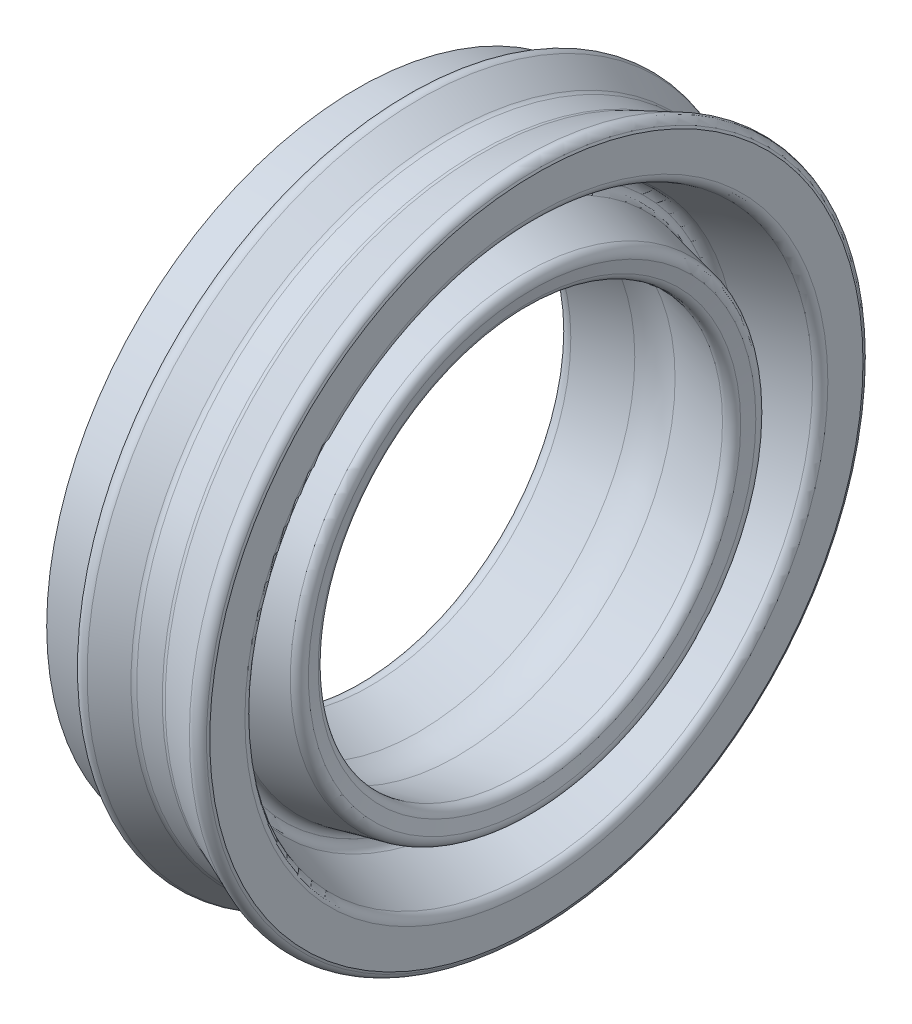
SolidWorks part; units mm, degrees
ref_plane "Alzado" through (0, 0, 0) normal (0, 0, 1) x (1, 0, 0)
ref_plane "Planta" through (0, 0, 0) normal (0, 1, 0) x (1, 0, 0)
ref_plane "Vista lateral" through (0, 0, 0) normal (1, 0, 0) x (0, 0, -1)
sketch "Croquis1" plane through (0, 0, 0) normal (0, 1, 0) x (1, 0, 0)
  line L0 (0, 0) -> (0, 6) construction
  line L1 (82.3658, 126.2926) -> (445.0325, 126.2926) construction
  line L2 (78.3557, 118.4737) -> (441.0224, 118.4737) construction
  line L3 (-2.1525, 8.367) -> (-1.0917, 8.367)
  line L4 (-1.0917, 8.367) -> (-0.805, 8.8728)
  line L5 (-0.4643, 8.9671) -> (0.2914, 8.5388)
  line L6 (0.4147, 8.5064) -> (1.1006, 8.5064)
  line L7 (1.1969, 8.5257) -> (2.3184, 8.994)
  line L8 (2.6455, 8.8596) -> (2.6711, 8.7983)
  line L9 (2.6711, 8.7983) -> (2.6711, 7.8514)
  line L10 (2.4959, 7.6128) -> (0.9249, 7.12)
  line L11 (0.7497, 6.8814) -> (0.7497, 6.8801)
  line L12 (0.9459, 6.636) -> (2.366, 6.3231)
  line L13 (2.5563, 6.0252) -> (2.4829, 5.6919)
  line L14 (2.1831, 5.502) -> (0.5274, 5.8797)
  line L15 (-0.5161, 5.8381) -> (-1.8277, 5.4266)
  line L16 (-2.1525, 5.6651) -> (-2.1525, 6.0858)
  line L17 (-1.9774, 6.3243) -> (-0.5906, 6.7594)
  line L18 (-0.5906, 6.7594) -> (-0.5906, 6.815)
  line L19 (-0.8406, 7.065) -> (-2.1525, 7.065)
  line L20 (-2.1525, 7.065) -> (-2.1525, 8.367)
  line L21 (0, 0) -> (-6.3209, 0) construction
  arc A0 (-0.4643, 8.9671) -> (-0.805, 8.8728) centre (-0.5875, 8.7496) ccw
  arc A1 (2.6455, 8.8596) -> (2.3184, 8.994) centre (2.4148, 8.7633) ccw
  arc A2 (0.4147, 8.5064) -> (0.2914, 8.5388) centre (0.4147, 8.7564) cw
  arc A3 (1.1969, 8.5257) -> (1.1006, 8.5064) centre (1.1006, 8.7564) cw
  arc A4 (2.6711, 7.8514) -> (2.4959, 7.6128) centre (2.4211, 7.8514) cw
  arc A5 (0.9249, 7.12) -> (0.7497, 6.8814) centre (0.9997, 6.8814) ccw
  arc A6 (0.7497, 6.8801) -> (0.9459, 6.636) centre (0.9997, 6.8801) ccw
  arc A7 (2.5563, 6.0252) -> (2.366, 6.3231) centre (2.3122, 6.079) ccw
  arc A8 (2.4829, 5.6919) -> (2.1831, 5.502) centre (2.2387, 5.7457) cw
  arc A9 (0.5274, 5.8797) -> (-0.5161, 5.8381) centre (0.0826, 3.9298) ccw
  arc A10 (-2.1525, 6.0858) -> (-1.9774, 6.3243) centre (-1.9025, 6.0858) cw
  arc A11 (-1.8277, 5.4266) -> (-2.1525, 5.6651) centre (-1.9025, 5.6651) cw
  arc A12 (-0.5906, 6.815) -> (-0.8406, 7.065) centre (-0.8406, 6.815) ccw
  dimension "D2" = 0.25
  dimension "D3" = 0.25
  dimension "D4" = 0.25
  dimension "D5" = 0.25
  dimension "D6" = 0.25
  dimension "D7" = 0.25
  dimension "D8" = 0.25
  dimension "D9" = 0.25
  dimension "D10" = 0.25
  dimension "D11" = 2
  dimension "D12" = 0.25
  dimension "D13" = 0.25
revolve "Revolución1" add sketch "Croquis1" angle 360 about L21
